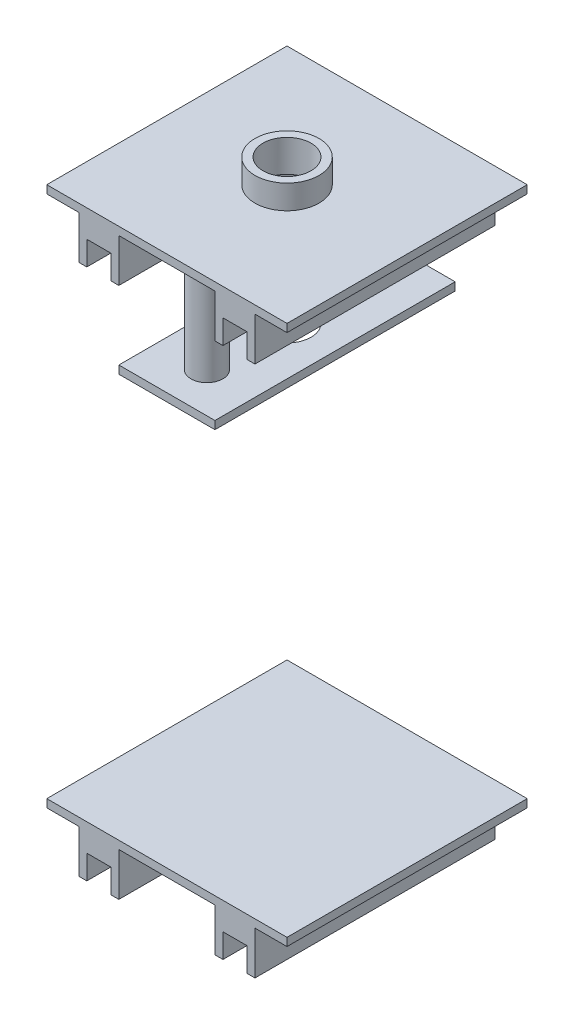
SolidWorks part; units mm, degrees
material "自定义塑料"
ref_plane "前视基准面" through (0, 0, 0) normal (0, 0, 1) x (1, 0, 0)
ref_plane "上视基准面" through (0, 0, 0) normal (0, 1, 0) x (1, 0, 0)
ref_plane "右视基准面" through (0, 0, 0) normal (1, 0, 0) x (0, 0, -1)
sketch "草图1" plane through (0, 0, 0) normal (0, 1, 0) x (1, 0, 0)
  line L1 (0, 0) -> (150, 0)
  line L2 (0, 0) -> (0, 150)
  line L3 (0, 150) -> (150, 150)
  line L4 (150, 0) -> (150, 150)
  dimension "D1" = 150
  dimension "D2" = 150
extrude "凸台-拉伸1" add sketch "草图1" along normal blind 5
sketch "草图2" plane through (0, 0, 0) normal (0, -1, 0) x (-1, 0, 0)
  line L0 (0, 0) -> (-20, 0)
  line L1 (0, 0) -> (-150, 0) construction
  line L2 (-150, 0) -> (-130, 0)
  line L3 (-150, 150) -> (0, 150) construction
  line L4 (-20, 0) -> (-45, 0)
  line L5 (-20, 0) -> (-20, 150)
  line L6 (-20, 150) -> (-45, 150)
  line L7 (-45, 0) -> (-45, 150)
  line L9 (-130, 0) -> (-105, 0)
  line L10 (-130, 0) -> (-130, 150)
  line L11 (-130, 150) -> (-105, 150)
  line L12 (-105, 0) -> (-105, 150)
  dimension "D1" = 20
  dimension "D2" = 20
  dimension "D3" = 25
  dimension "D4" = 25
extrude "凸台-拉伸2" add sketch "草图2" along normal blind 27 contours L9 L12 L11 L10 | L5 L6 L7 L4
sketch "草图3" plane through (0, -27, 0) normal (0, -1, 0) x (1, 0, 0)
  line L0 (20, 0) -> (25, 0)
  line L1 (20, 0) -> (45, 0) construction
  line L2 (20, -150) -> (45, -150) construction
  line L3 (25, 0) -> (40, 0)
  line L4 (25, 0) -> (25, -150)
  line L5 (25, -150) -> (40, -150)
  line L6 (40, 0) -> (40, -150)
  line L7 (130, 0) -> (125, 0)
  line L8 (130, 0) -> (105, 0) construction
  line L9 (130, -150) -> (105, -150) construction
  line L10 (125, 0) -> (110, 0)
  line L11 (125, 0) -> (125, -150)
  line L12 (125, -150) -> (110, -150)
  line L13 (110, 0) -> (110, -150)
extrude "切除-拉伸1" cut sketch "草图3" against normal blind 15
sketch "草图4" plane through (0, 5, 0) normal (0, 1, 0) x (1, 0, 0)
  line L5 (45, 35) -> (105, 35)
  line L6 (45, 35) -> (45, 115)
  line L7 (45, 115) -> (105, 115)
  line L8 (105, 35) -> (105, 115)
  line L9 (105, 115) -> (45, 115)
  dimension "D3" = 60
  dimension "D4" = 80
sketch "草图5" plane through (150, 0, 0) normal (1, 0, 0) x (0, 0, -1)
  line L0 (0, 0) -> (0, 332)
  line L2 (0, 332) -> (150, 332)
  line L3 (0, 332) -> (0, 337)
  line L4 (0, 337) -> (150, 337)
  line L5 (150, 332) -> (150, 337)
extrude "凸台-拉伸3" add sketch "草图5" against normal blind 150 contours L2 L5 L4 L3
sketch "草图6" plane through (0, 332, 0) normal (0, -1, 0) x (1, 0, 0)
  line L0 (150, -150) -> (130, -150)
  line L1 (0, -150) -> (150, -150) construction
  line L2 (0, -150) -> (20, -150)
  line L3 (0, 0) -> (150, 0) construction
  line L4 (130, -150) -> (105, -150)
  line L5 (130, -150) -> (130, 0)
  line L6 (130, 0) -> (105, 0)
  line L7 (105, -150) -> (105, 0)
  line L9 (20, -150) -> (45, -150)
  line L10 (20, -150) -> (20, 0)
  line L11 (20, 0) -> (45, 0)
  line L12 (45, -150) -> (45, 0)
  dimension "D1" = 20
  dimension "D2" = 20
  dimension "D3" = 25
  dimension "D4" = 25
extrude "凸台-拉伸4" add sketch "草图6" along normal blind 27 contours L10 L11 L12 L9 | L4 L7 L6 L5
sketch "草图7" plane through (0, 305, 0) normal (0, -1, 0) x (-1, 0, 0)
  line L0 (-130, 150) -> (-125, 150)
  line L1 (-130, 150) -> (-105, 150) construction
  line L2 (-130, 0) -> (-105, 0) construction
  line L3 (-125, 150) -> (-110, 150)
  line L4 (-125, 150) -> (-125, 0)
  line L5 (-125, 0) -> (-110, 0)
  line L6 (-110, 150) -> (-110, 0)
  line L7 (-20, 150) -> (-25, 150)
  line L8 (-20, 150) -> (-45, 150) construction
  line L9 (-20, 0) -> (-45, 0) construction
  line L10 (-25, 150) -> (-40, 150)
  line L11 (-25, 150) -> (-25, 0)
  line L12 (-25, 0) -> (-40, 0)
  line L13 (-40, 150) -> (-40, 0)
extrude "切除-拉伸3" cut sketch "草图7" against normal blind 15 contours L11 L12 L13 L10 | L4 L5 L6 L3
sketch "草图8" plane through (0, 337, 0) normal (0, 1, 0) x (1, 0, 0)
  circle A0 centre (75, 75) radius 20
  dimension "D3" = 40
extrude "凸台-拉伸5" add sketch "草图8" along normal blind 15
sketch "草图9" plane through (0, 332, 0) normal (0, -1, 0) x (-1, 0, 0)
  circle A0 centre (-75, 25) radius 10
  circle A1 centre (-75, 125) radius 10
  dimension "D3" = 20
  dimension "D5" = 20
extrude "凸台-拉伸6" add sketch "草图9" along normal blind 70 contours A1 | A0
sketch "草图10" plane through (0, 262, 0) normal (0, -1, 0) x (1, 0, 0)
  line L3 (75, 0) -> (105, 0)
  line L4 (105, -125) -> (105, 0)
  line L7 (75, 0) -> (45, 0)
  line L8 (45, -125) -> (45, 0)
  line L10 (105, -125) -> (105, -150)
  line L11 (105, -150) -> (45, -150)
  line L12 (45, -125) -> (45, -150)
  dimension "D3" = 30
  dimension "D1" = 125
  dimension "D2" = 30
  dimension "D4" = 25
extrude "凸台-拉伸7" add sketch "草图10" along normal blind 5
sketch "草图12" plane through (0, 352, 0) normal (0, 1, 0) x (1, 0, 0)
  circle A0 centre (75, 75) radius 15
  dimension "D1" = 30
extrude "切除-拉伸4" cut sketch "草图12" against normal blind 95
